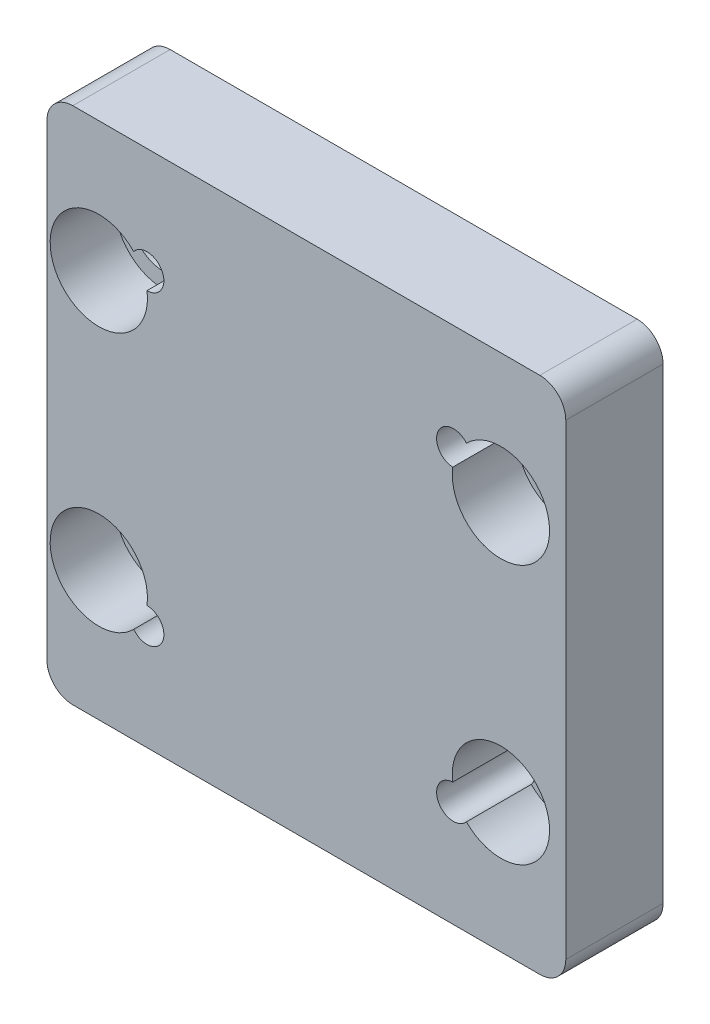
SolidWorks part; units mm, degrees
ref_plane "Front Plane" through (0, 0, 0) normal (0, 0, 1) x (1, 0, 0)
ref_plane "Top Plane" through (0, 0, 0) normal (0, 1, 0) x (1, 0, 0)
ref_plane "Right Plane" through (0, 0, 0) normal (1, 0, 0) x (0, 0, -1)
sketch "Sketch1" plane through (0, 0, 0) normal (0, 0, 1) x (1, 0, 0)
  line L1 (0, 0) -> (50.8, 0)
  line L2 (0, 0) -> (0, 50.8)
  line L3 (0, 50.8) -> (50.8, 50.8)
  line L4 (50.8, 0) -> (50.8, 50.8)
  dimension "D1" = 50.8
  dimension "D2" = 50.8
extrude "Boss-Extrude1" add sketch "Sketch1" along normal blind 9.525
hole_wizard "Tap Drill for M4x0.7 Tap1" positions "Sketch2" profile "Sketch3" hole size "M4x0.7" standard "ANSI Metric" end condition through all
sketch "Sketch2" plane through (0, 0, 9.525) normal (0, 0, 1) x (1, 0, 0)
  line L0 (39.8, 50.8) -> (39.8, 0) construction
  line L1 (50.8, 50.8) -> (0, 50.8) construction
  line L2 (0, 0) -> (50.8, 0) construction
  line L3 (50.8, 0) -> (50.8, 50.8) construction
  line L4 (9.8, 50.8) -> (9.8, 0) construction
  line L6 (0, 25.4) -> (50.8, 25.4) construction
  line L7 (0, 50.8) -> (0, 0) construction
  point P9 (39.8, 40.4)
  point P23 (9.8, 40.4)
  point P26 (9.8, 10.4)
  point P28 (39.8, 10.4)
  dimension "D1" = 11
  dimension "D2" = 30
  dimension "D3" = 15
  dimension "D4" = 15
  dimension "D5" = 15
sketch "Sketch3" plane through (39.8, 10.4, 9.525) normal (1, 0, 0) x (0, -1, 0)
  line L0 (0, 0) -> (0, 9.525)
  line L1 (0, 9.525) -> (1.65, 9.525)
  line L2 (1.65, 9.525) -> (1.65, 0)
  line L5 (1.65, 0) -> (0, 0)
  line L11 (0, -6.35) -> (0, 107.95) construction
  dimension "Thru Hole Dia." = 3.3
  dimension "Thru Hole Depth" = 9.525
hole_wizard "CBORE for 1/4 Socket Head Cap Screw1" positions "Sketch6" profile "Sketch5" counterbore size "1/4" standard "ANSI Inch" end condition through all
sketch "Sketch6" plane through (0, 0, 9.525) normal (0, 0, 1) x (1, 0, 0)
  line L8 (0, 50.8) -> (50.8, 0) construction
  line L10 (5.08, 12.7) -> (44.45, 12.7) construction
  line L11 (5.08, 12.7) -> (5.08, 38.1) construction
  line L12 (5.08, 38.1) -> (44.45, 38.1) construction
  line L13 (44.45, 12.7) -> (44.45, 38.1) construction
  line L14 (5.08, 12.7) -> (44.45, 38.1) construction
  line L15 (5.08, 38.1) -> (44.45, 12.7) construction
  circle A0 centre (39.8, 40.4) radius 1.65 construction
  point P107 (44.45, 38.1)
  point P194 (5.08, 12.7)
  point P195 (5.08, 38.1)
  point P196 (44.45, 12.7)
  dimension "D1" = 25.4
  dimension "D2" = 39.37
  dimension "D3" = 4.65
  dimension "D4" = 2.3
sketch "Sketch5" plane through (44.45, 12.7, 9.525) normal (1, 0, 0) x (0, -1, 0)
  line L0 (0, 0) -> (0, 9.525)
  line L1 (0, 9.525) -> (3.2639, 9.525)
  line L3 (3.2639, 9.525) -> (3.2639, 6.35)
  line L4 (3.2639, 6.35) -> (4.7625, 6.35)
  line L5 (4.7625, 6.35) -> (4.7625, 0)
  line L7 (4.7625, 0) -> (0, 0)
  line L11 (0, -6.35) -> (0, 107.95) construction
  dimension "Thru Hole Dia." = 6.5278
  dimension "Thru Hole Depth" = 9.525
  dimension "C'Bore Dia." = 9.525
  dimension "C'Bore Depth" = 6.35
fillet "Fillet1" radius 2.54 4 edges at (50.8, 0, 4.7625) (0, 0, 4.7625) (0, 50.8, 4.7625) (50.8, 50.8, 4.7625)
